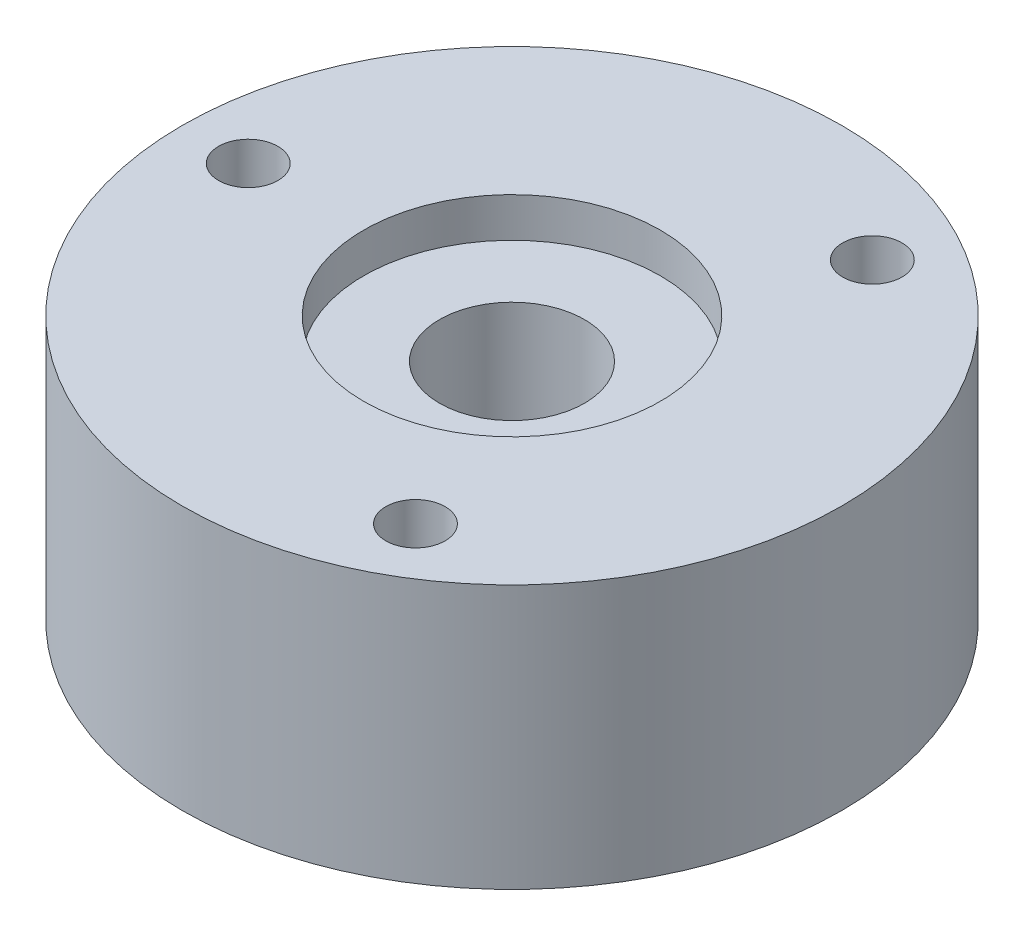
SolidWorks part; units mm, degrees
ref_plane "Front Plane" through (0, 0, 0) normal (0, 0, 1) x (1, 0, 0)
ref_plane "Top Plane" through (0, 0, 0) normal (0, 1, 0) x (1, 0, 0)
ref_plane "Right Plane" through (0, 0, 0) normal (1, 0, 0) x (0, 0, -1)
sketch "Sketch1" plane through (0, 0, 0) normal (0, 1, 0) x (1, 0, 0)
  line L0 (0, 0) -> (12.5, -21.6506) construction
  line L1 (0, 0) -> (25, 0) construction
  circle A0 centre (0, 0) radius 25
  circle A1 centre (0, 0) radius 5.5
  point P5 (7.5, -12.9904)
  dimension "D1" = 50
  dimension "D2" = 11
  dimension "D3" = 60
  dimension "D4" = 15
extrude "Boss-Extrude1" add sketch "Sketch1" along normal blind 20
sketch "Sketch2" plane through (0, 20, 0) normal (0, 1, 0) x (1, 0, 0)
  circle A0 centre (0, 0) radius 11.25
  dimension "D1" = 22.5
extrude "Cut-Extrude2" cut sketch "Sketch2" against normal blind 3
sketch "Sketch3" plane through (0, 20, 0) normal (0, 1, 0) x (1, 0, 0)
  line L0 (0, 0) -> (25, 0) construction
  line L1 (0, 0) -> (12.5, -21.6506) construction
  circle A0 centre (0, 0) radius 25 construction
  circle A1 centre (10, -17.3205) radius 2.25
  point P6 (10, -17.3205)
  dimension "D3" = 4.5
  dimension "D1" = 60
  dimension "D2" = 20
extrude "Cut-Extrude3" cut sketch "Sketch3" against normal up to surface (20 mm away) up to face at (0, 0, 25)
pattern_circular "CirPattern1" count 3 over 360 about axis through (0, 0, 0) along (0, 1, 0) of "Cut-Extrude3"
